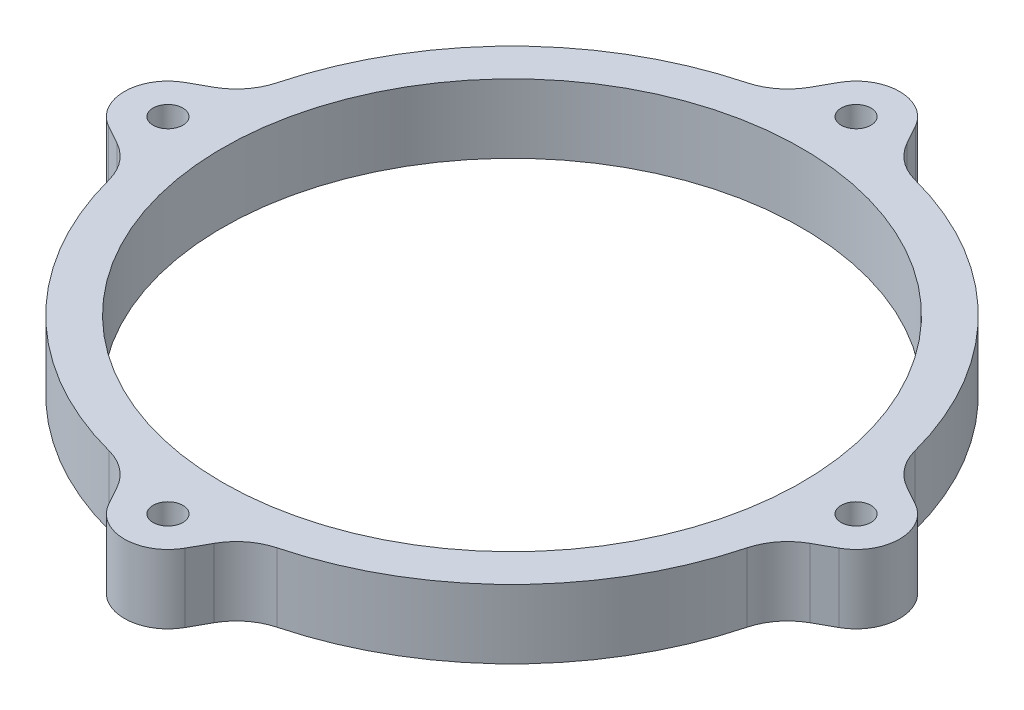
SolidWorks part; units mm, degrees
ref_plane "正面" through (0, 0, 0) normal (0, 0, 1) x (1, 0, 0)
ref_plane "平面" through (0, 0, 0) normal (0, 1, 0) x (1, 0, 0)
ref_plane "右側面" through (0, 0, 0) normal (1, 0, 0) x (0, 0, -1)
sketch "ｽｹｯﾁ1" plane through (0, 0, 0) normal (0, 1, 0) x (1, 0, 0)
  line L0 (0, 0) -> (0, 60) construction
  line L1 (-6.6411, 63.6954) -> (-10.6411, 56.5068)
  line L2 (6.6411, 63.6954) -> (10.6411, 56.5068)
  line L3 (63.6954, 6.6411) -> (56.5068, 10.6411)
  line L4 (63.6954, -6.6411) -> (56.5068, -10.6411)
  line L5 (6.6411, -63.6954) -> (10.6411, -56.5068)
  line L6 (-6.6411, -63.6954) -> (-10.6411, -56.5068)
  line L7 (-63.6954, -6.6411) -> (-56.5068, -10.6411)
  line L8 (-63.6954, 6.6411) -> (-56.5068, 10.6411)
  line L9 (-60, 0) -> (0, 0) construction
  line L10 (0, 0) -> (0, -60) construction
  arc A0 (-10.6411, 56.5068) -> (-56.5068, 10.6411) centre (0, 0) ccw
  circle A1 centre (0, 0) radius 50.5
  circle A2 centre (0, 60) radius 2.6
  arc A3 (6.6411, 63.6954) -> (-6.6411, 63.6954) centre (0, 60) ccw
  circle A4 centre (0, 60) radius 7.6 construction
  circle A5 centre (60, 0) radius 2.6
  arc A6 (63.6954, -6.6411) -> (63.6954, 6.6411) centre (60, 0) ccw
  circle A7 centre (0, -60) radius 2.6
  arc A8 (-6.6411, -63.6954) -> (6.6411, -63.6954) centre (0, -60) ccw
  circle A9 centre (-60, 0) radius 2.6
  arc A10 (-63.6954, 6.6411) -> (-63.6954, -6.6411) centre (-60, 0) ccw
  arc A11 (-56.5068, -10.6411) -> (-10.6411, -56.5068) centre (0, 0) ccw
  arc A12 (10.6411, -56.5068) -> (56.5068, -10.6411) centre (0, 0) ccw
  arc A13 (56.5068, 10.6411) -> (10.6411, 56.5068) centre (0, 0) ccw
  dimension "D1" = 101
  dimension "D2" = 115
  dimension "D3" = 60
  dimension "D4" = 5.2
  dimension "D6" = 4
  dimension "D5" = 5
  dimension "D7" = 4
extrude "ﾎﾞｽ - 押し出し1" add sketch "ｽｹｯﾁ1" along normal blind 12
fillet "ﾌｨﾚｯﾄ1" radius 10 8 edges at (56.5068, 6, 10.6411) (56.5068, 6, -10.6411) (10.6411, 6, -56.5068) (-10.6411, 6, -56.5068) (-56.5068, 6, -10.6411) (-56.5068, 6, 10.6411) (-10.6411, 6, 56.5068) (10.6411, 6, 56.5068)
